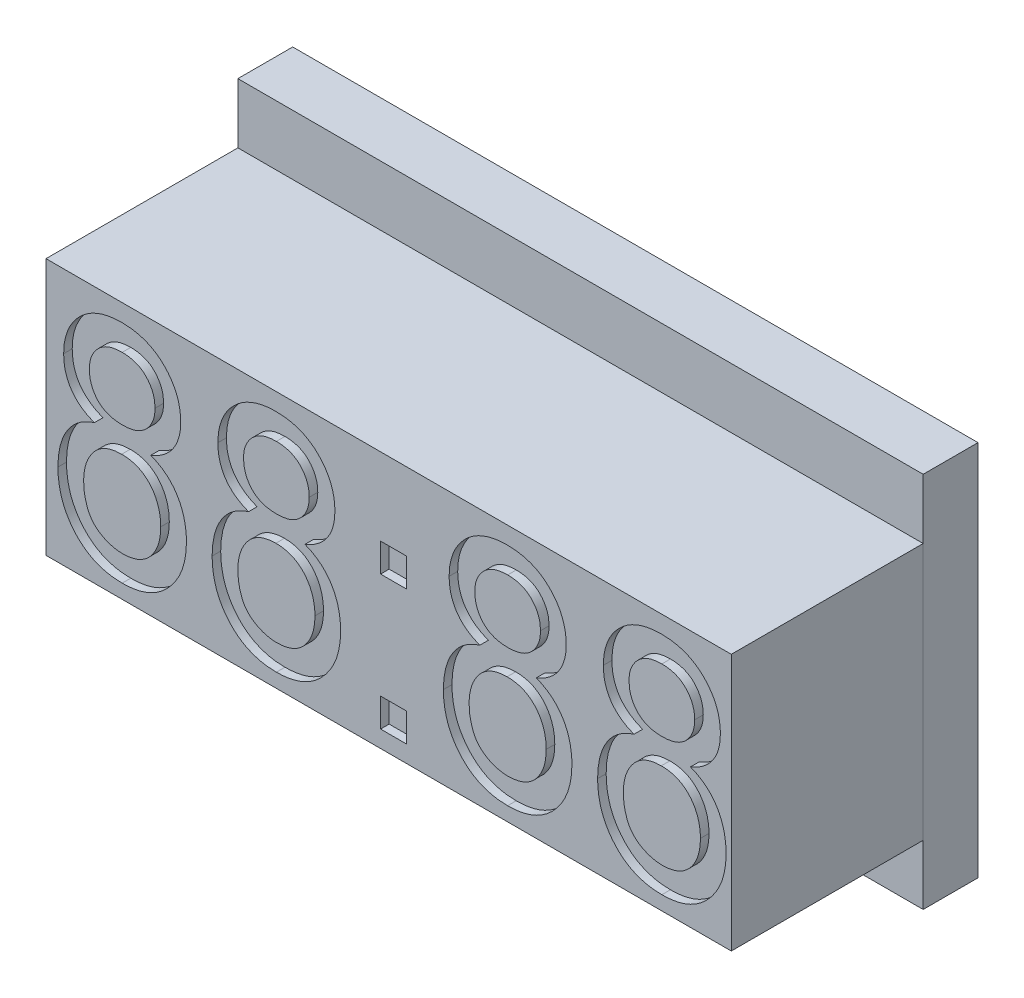
SolidWorks part; units mm, degrees
material "ABS"
ref_plane "Front Plane" through (0, 0, 0) normal (0, 0, 1) x (1, 0, 0)
ref_plane "Top Plane" through (0, 0, 0) normal (0, 1, 0) x (1, 0, 0)
ref_plane "Right Plane" through (0, 0, 0) normal (1, 0, 0) x (0, 0, -1)
sketch "Sketch1" plane through (0, 0, 0) normal (0, 0, 1) x (1, 0, 0)
  line L1 (0, 0) -> (50.8, 0)
  line L2 (0, 0) -> (0, 19.05)
  line L3 (0, 19.05) -> (50.8, 19.05)
  line L4 (50.8, 0) -> (50.8, 19.05)
  dimension "D1" = 19.05
  dimension "D2" = 50.8
extrude "Boss-Extrude1" add sketch "Sketch1" along normal blind 14.224
sketch "Sketch2" plane through (0, 0, 14.224) normal (0, 0, 1) x (1, 0, 0)
  text T0 "88:88" font "Arial" height 16.51
extrude "Cut-Extrude1" cut sketch "Sketch2" against normal blind 0.635
sketch "Sketch3" plane through (0, 0, 0) normal (0, 0, -1) x (-1, 0, 0)
  line L0 (-50.8, 19.05) -> (0, 19.05) construction
  line L1 (-50.8, 23.495) -> (0, 23.495)
  line L2 (-50.8, 23.495) -> (-50.8, -4.445)
  line L3 (-50.8, -4.445) -> (0, -4.445)
  line L4 (0, 23.495) -> (0, -4.445)
  line L5 (-50.8, 0) -> (-50.8, 19.05) construction
  dimension "D1" = 50.8
  dimension "D2" = 27.94
  dimension "D3" = 4.445
extrude "Boss-Extrude2" add sketch "Sketch3" along normal blind 4.064 separate body
